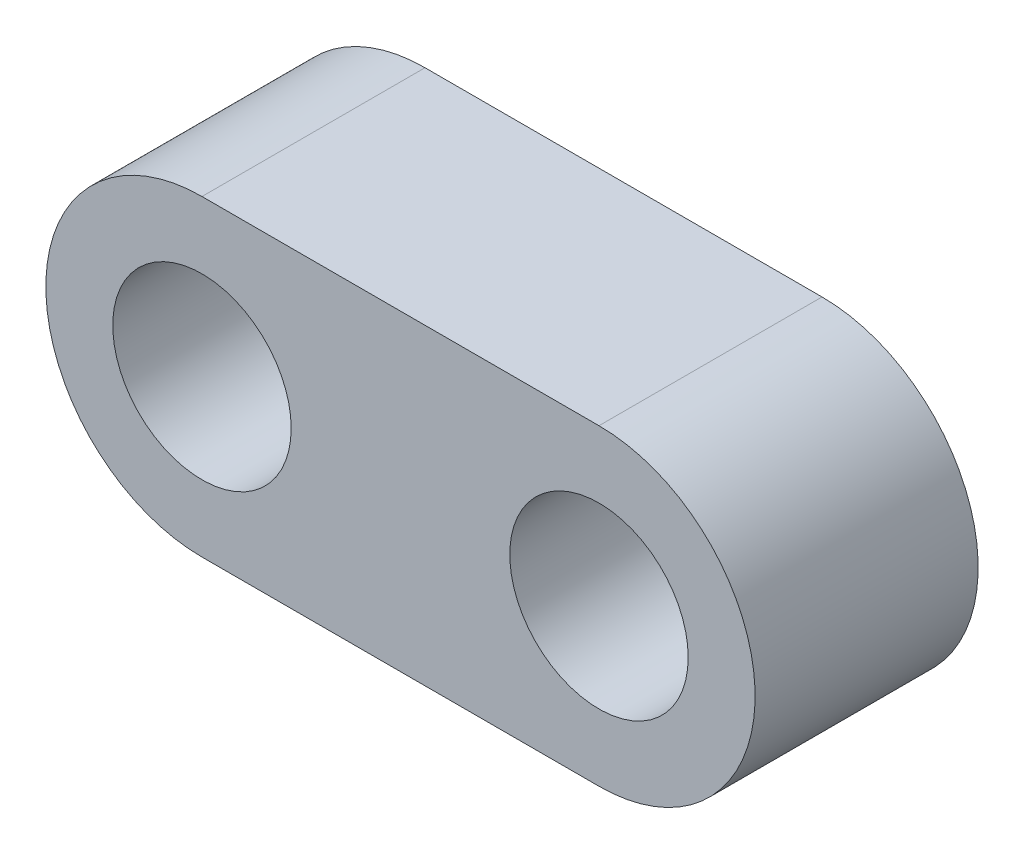
SolidWorks part; units mm, degrees
ref_plane "前视基准面" through (0, 0, 0) normal (0, 0, 1) x (1, 0, 0)
ref_plane "上视基准面" through (0, 0, 0) normal (0, 1, 0) x (1, 0, 0)
ref_plane "右视基准面" through (0, 0, 0) normal (1, 0, 0) x (0, 0, -1)
other "Configuration Table"
sketch "草图2" plane through (0, 0, 0) normal (0, 0, 1) x (1, 0, 0)
  line L0 (0, 0) -> (89, 0)
  line L1 (0, 35) -> (89, 35)
  line L3 (89, -35) -> (0, -35)
  arc A0 (0, 35) -> (0, -35) centre (0, 0) ccw
  arc A1 (89, -35) -> (89, 35) centre (89, 0) ccw
  circle A2 centre (0, 0) radius 20
  circle A3 centre (89, 0) radius 20
  dimension "D1" = 35
  dimension "D2" = 40
  dimension "D3" = 89
extrude "凸台-拉伸1" add sketch "草图2" along normal blind 50
